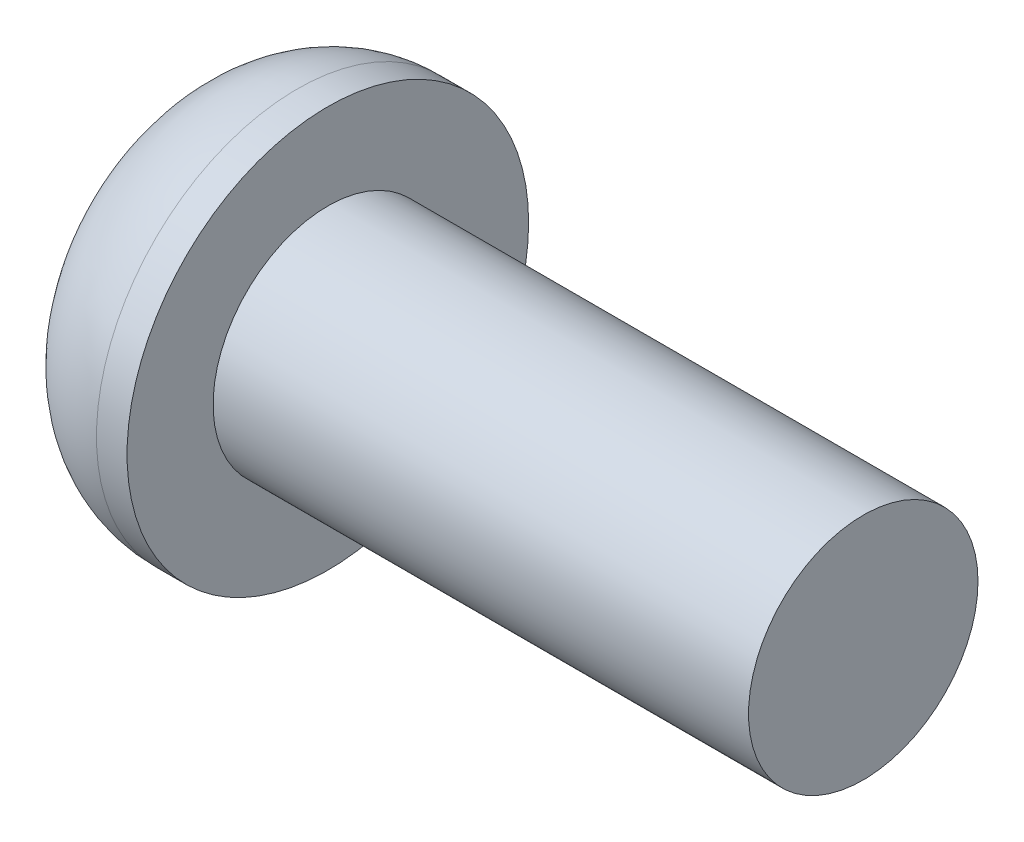
SolidWorks part; units mm, degrees
ref_plane "Front Plane" through (0, 0, 0) normal (0, 0, 1) x (1, 0, 0)
ref_plane "Top Plane" through (0, 0, 0) normal (0, 1, 0) x (1, 0, 0)
ref_plane "Right Plane" through (0, 0, 0) normal (1, 0, 0) x (0, 0, -1)
sketch "Sketch1" plane through (0, 0, 0) normal (0, 0, 1) x (1, 0, 0)
  line L0 (0, 0) -> (0, 2.05)
  line L1 (3.2, 5.25) -> (4, 5.25)
  line L2 (4, 5.25) -> (4, 3)
  line L3 (4, 3) -> (18, 3)
  line L4 (18, 3) -> (18, 0)
  line L5 (18, 0) -> (0, 0)
  line L6 (0, 0) -> (-9179.3886, 0) construction
  arc A0 (0, 2.05) -> (3.2, 5.25) centre (3.2, 2.05) cw
  dimension "D3" = 0.8
  dimension "D1" = 10.5
  dimension "D2" = 4
  dimension "D4" = 6
  dimension "D5" = 14
revolve "Revolve1" add sketch "Sketch1" angle 360 about L6
sketch "Sketch2" plane through (0, 0, 0) normal (-1, 0, 0) x (0, 0, 1)
  line L1 (2.3094, 0) -> (1.1547, 2)
  line L2 (1.1547, 2) -> (-1.1547, 2)
  line L3 (-1.1547, 2) -> (-2.3094, 0)
  line L4 (-2.3094, 0) -> (-1.1547, -2)
  line L5 (-1.1547, -2) -> (1.1547, -2)
  line L6 (1.1547, -2) -> (2.3094, 0)
  circle A0 centre (0, 0) radius 2 construction
  dimension "D1" = 4
extrude "Cut-Extrude1" cut sketch "Sketch2" against normal blind 4.2
